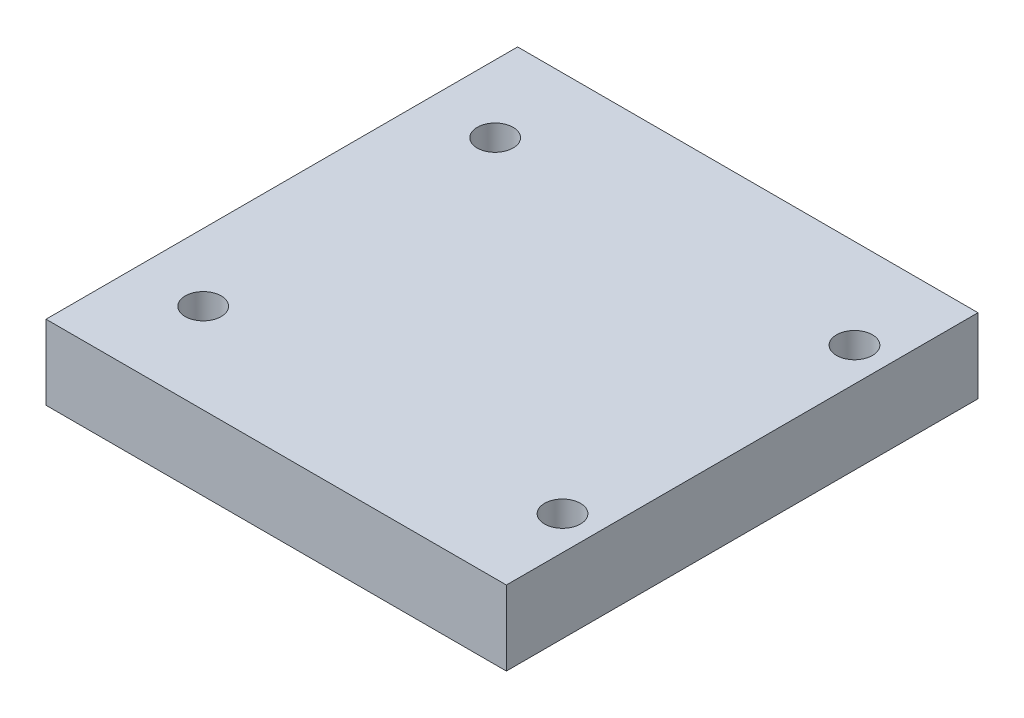
SolidWorks part; units mm, degrees
ref_plane "Front Plane" through (0, 0, 0) normal (0, 0, 1) x (1, 0, 0)
ref_plane "Top Plane" through (0, 0, 0) normal (0, 1, 0) x (1, 0, 0)
ref_plane "Right Plane" through (0, 0, 0) normal (1, 0, 0) x (0, 0, -1)
sketch "Sketch1" plane through (0, 0, 0) normal (0, 1, 0) x (1, 0, 0)
  line L1 (-59.5172, -24.9252) -> (5.5703, -24.9252)
  line L2 (-59.5172, -24.9252) -> (-59.5172, 41.7498)
  line L3 (-59.5172, 41.7498) -> (5.5703, 41.7498)
  line L4 (5.5703, -24.9252) -> (5.5703, 41.7498)
extrude "Boss-Extrude2" add sketch "Sketch1" along normal blind 10.541
sketch "Sketch3" plane through (0, 10.541, 0) normal (0, 1, 0) x (1, 0, 0)
  line L0 (5.5703, 41.7498) -> (-59.5172, 41.7498) construction
  line L1 (-59.5172, 41.7498) -> (-59.5172, -24.9252) construction
  circle A0 centre (-49.9922, 29.0498) radius 2.54
  circle A1 centre (0.8078, 29.0498) radius 2.54
  circle A2 centre (-49.9922, -12.2252) radius 2.54
  circle A3 centre (0.8078, -12.2252) radius 2.54
  point P8 (-5.1642, 29.0498)
  point P11 (-49.9922, -12.8135)
  point P14 (0, 0)
  point P15 (0.8078, -12.2252)
  dimension "D1" = 12.7
  dimension "D2" = 9.525
  dimension "D3" = 50.8
  dimension "D6" = 41.275
  dimension "D4" = 41.275
  dimension "D5" = 50.8
extrude "Cut-Extrude1" cut sketch "Sketch3" against normal through all both and the other way through all
